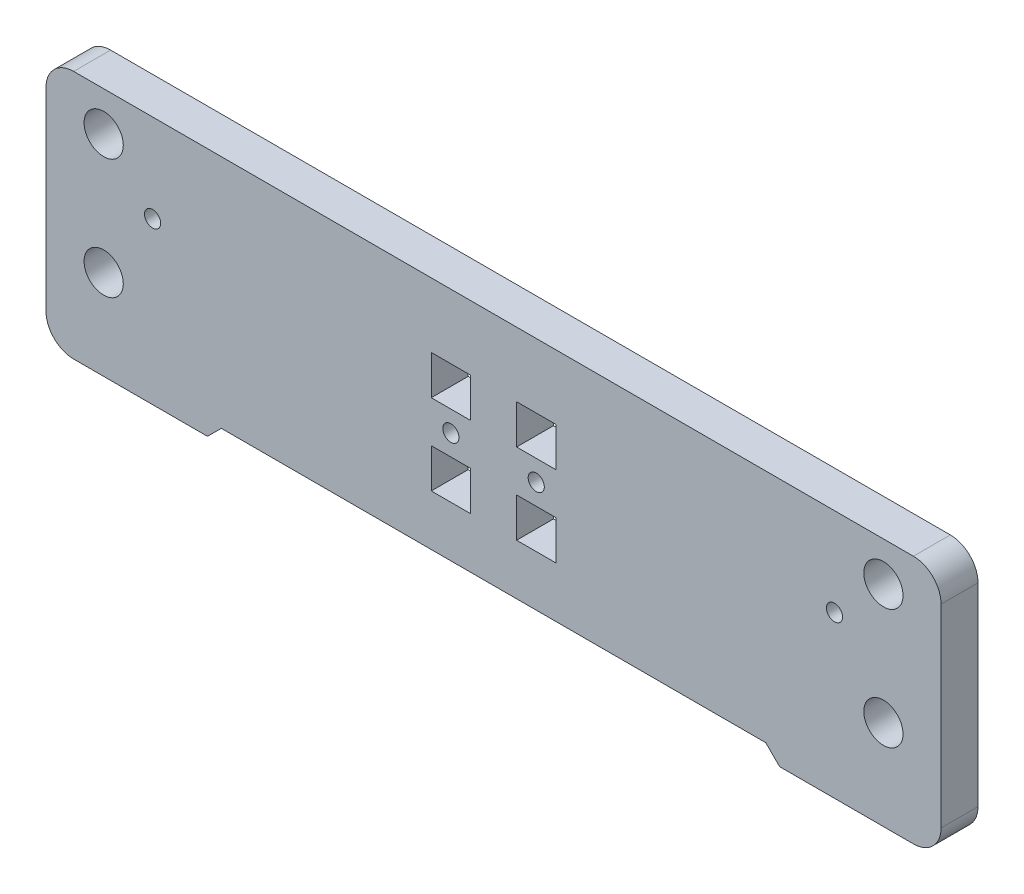
SolidWorks part; units mm, degrees
ref_plane "Front Plane" through (0, 0, 0) normal (0, 0, 1) x (1, 0, 0)
ref_plane "Top Plane" through (0, 0, 0) normal (0, 1, 0) x (1, 0, 0)
ref_plane "Right Plane" through (0, 0, 0) normal (1, 0, 0) x (0, 0, -1)
sketch "Sketch1" plane through (0, 0, 0) normal (0, 0, 1) x (1, 0, 0)
  line L0 (88.5829, 44.8981) -> (97.0829, 44.8981)
  line L1 (97.0829, 44.8981) -> (97.0829, 36.3981)
  line L2 (97.0829, 36.3981) -> (88.5829, 36.3981)
  line L3 (88.5829, 36.3981) -> (88.5829, 44.8981)
  line L4 (115.5829, 44.8981) -> (107.0829, 44.8981)
  line L5 (107.0829, 44.8981) -> (107.0829, 36.3981)
  line L6 (107.0829, 36.3981) -> (115.5829, 36.3981)
  line L7 (115.5829, 36.3981) -> (115.5829, 44.8981)
  line L8 (88.5829, 27.3981) -> (97.0829, 27.3981)
  line L9 (97.0829, 27.3981) -> (97.0829, 18.8981)
  line L10 (97.0829, 18.8981) -> (88.5829, 18.8981)
  line L11 (88.5829, 18.8981) -> (88.5829, 27.3981)
  line L12 (115.5829, 27.3981) -> (107.0829, 27.3981)
  line L13 (107.0829, 27.3981) -> (107.0829, 18.8981)
  line L14 (107.0829, 18.8981) -> (115.5829, 18.8981)
  line L15 (115.5829, 18.8981) -> (115.5829, 27.3981)
  line L16 (5.0829, 52.8981) -> (5.0829, 10.8981)
  line L17 (11.0829, 4.8981) -> (40.0829, 4.8981)
  line L18 (40.0829, 4.8981) -> (43.0829, 7.8981)
  line L19 (43.0829, 7.8981) -> (161.0829, 7.8981)
  line L20 (161.0829, 7.8981) -> (164.0829, 4.8981)
  line L21 (164.0829, 4.8981) -> (193.0829, 4.8981)
  line L22 (199.0829, 10.8981) -> (199.0829, 52.8981)
  line L23 (193.0829, 58.8981) -> (11.0829, 58.8981)
  line L24 (102.0829, 58.8981) -> (102.0829, 7.8981) construction
  circle A0 centre (186.5829, 50.3981) radius 4.25
  circle A1 centre (186.5829, 24.3981) radius 4.25
  circle A2 centre (17.5829, 50.3981) radius 4.25
  circle A3 centre (17.5829, 24.3981) radius 4.25
  circle A4 centre (92.8329, 31.8981) radius 1.75
  circle A5 centre (111.3329, 31.8981) radius 1.75
  arc A6 (5.0829, 10.8981) -> (11.0829, 4.8981) centre (11.0829, 10.8981) ccw
  arc A7 (193.0829, 4.8981) -> (199.0829, 10.8981) centre (193.0829, 10.8981) ccw
  arc A8 (199.0829, 52.8981) -> (193.0829, 58.8981) centre (193.0829, 52.8981) ccw
  arc A9 (11.0829, 58.8981) -> (5.0829, 52.8981) centre (11.0829, 52.8981) ccw
  dimension "D6" = 6
  dimension "D12" = 9.25
  dimension "D13" = 24
  dimension "D14" = 3.5
  dimension "D17" = 9.25
  dimension "D18" = 24
  dimension "D19" = 3.5
  dimension "D1" = 124
  dimension "D2" = 51
  dimension "D3" = 54
  dimension "D4" = 194
  dimension "D5" = 118
  dimension "D7" = 97
  dimension "D8" = 51
  dimension "D9" = 102.0829
  dimension "D10" = 5
  dimension "D11" = 5
  dimension "D15" = 5
  dimension "D16" = 5
extrude "Extrude1" add sketch "Sketch1" along normal blind 8
sketch "Sketch2" plane through (0, 0, 8) normal (0, 0, 1) x (1, 0, 0)
  line L0 (32.5829, 50.3981) -> (17.5829, 50.3981) construction
  line L1 (17.5829, 50.3981) -> (28.1895, 39.7915) construction
  line L2 (186.5829, 50.3981) -> (171.5829, 50.3981) construction
  line L3 (186.5829, 50.3981) -> (175.9763, 39.7915) construction
  circle A0 centre (17.5829, 50.3981) radius 15
  circle A1 centre (186.5829, 50.3981) radius 15
  circle A2 centre (28.1895, 39.7915) radius 1.75
  circle A3 centre (175.9763, 39.7915) radius 1.75
  dimension "D1" = 30
  dimension "D2" = 30
  dimension "D4" = 3.5
  dimension "D6" = 3.5
  dimension "D3" = 45
  dimension "D5" = 45
extrude "Extrude2" cut sketch "Sketch2" against normal blind 10 contours A3 | A2
